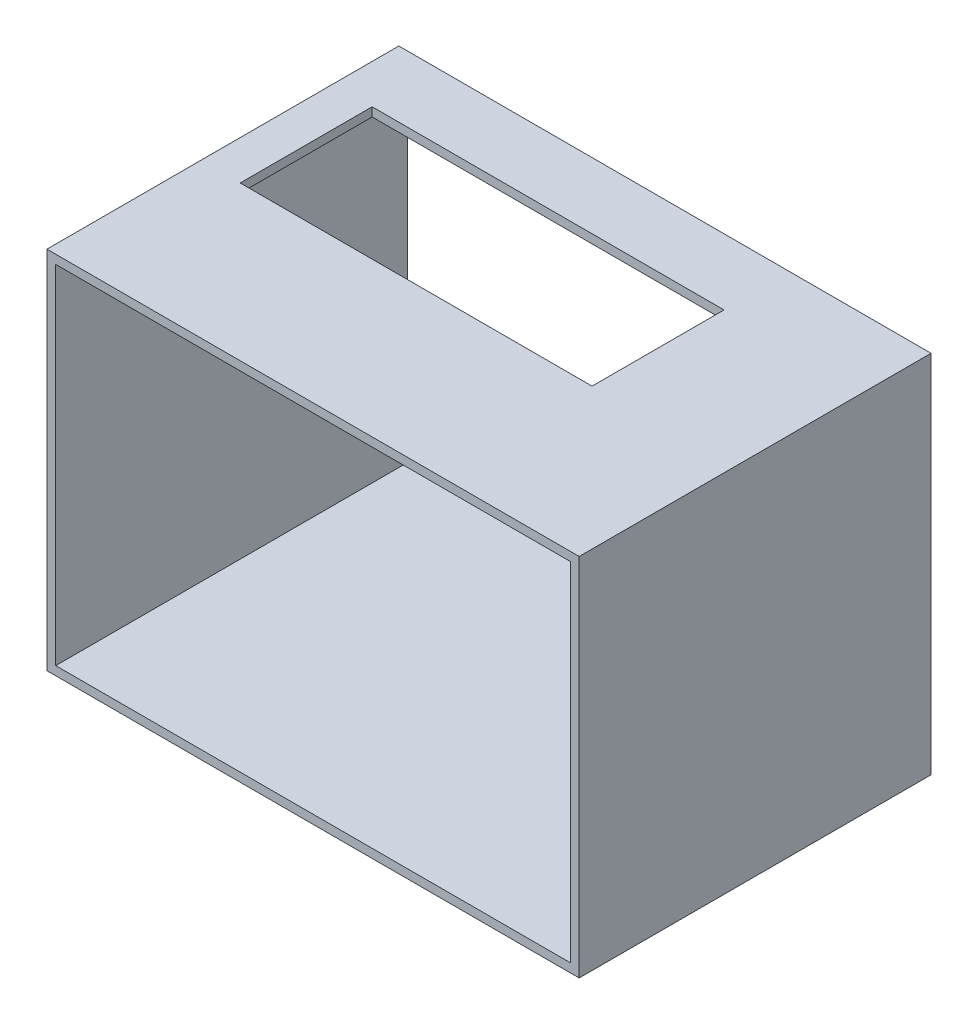
SolidWorks part; units mm, degrees
ref_plane "Front Plane" through (0, 0, 0) normal (0, 0, 1) x (1, 0, 0)
ref_plane "Top Plane" through (0, 0, 0) normal (0, 1, 0) x (1, 0, 0)
ref_plane "Right Plane" through (0, 0, 0) normal (1, 0, 0) x (0, 0, -1)
sketch "Sketch1" plane through (0, 0, 0) normal (0, 0, 1) x (1, 0, 0)
  line L1 (-40.1362, 31.6865) -> (80.8638, 31.6865)
  line L2 (-40.1362, 31.6865) -> (-40.1362, -51.3135)
  line L3 (-40.1362, -51.3135) -> (80.8638, -51.3135)
  line L4 (80.8638, 31.6865) -> (80.8638, -51.3135)
  line L5 (-38.1362, 29.6865) -> (78.8638, 29.6865)
  line L6 (-38.1362, 29.6865) -> (-38.1362, -49.3135)
  line L7 (-38.1362, -49.3135) -> (78.8638, -49.3135)
  line L8 (78.8638, 29.6865) -> (78.8638, -49.3135)
  dimension "D1" = 121
  dimension "D2" = 117
  dimension "D3" = 83
  dimension "D4" = 79
  dimension "D5" = 2
  dimension "D6" = 2
extrude "Boss-Extrude1" add sketch "Sketch1" along normal blind 80
sketch "Sketch2" plane through (0, 31.6865, 0) normal (0, 1, 0) x (1, 0, 0)
  line L1 (-31.2018, -15) -> (48.7982, -15)
  line L2 (-31.2018, -15) -> (-31.2018, -45)
  line L3 (-31.2018, -45) -> (48.7982, -45)
  line L4 (48.7982, -15) -> (48.7982, -45)
extrude "Cut-Extrude1" cut sketch "Sketch2" against normal blind 4 contours L2 L1 L4 L3
